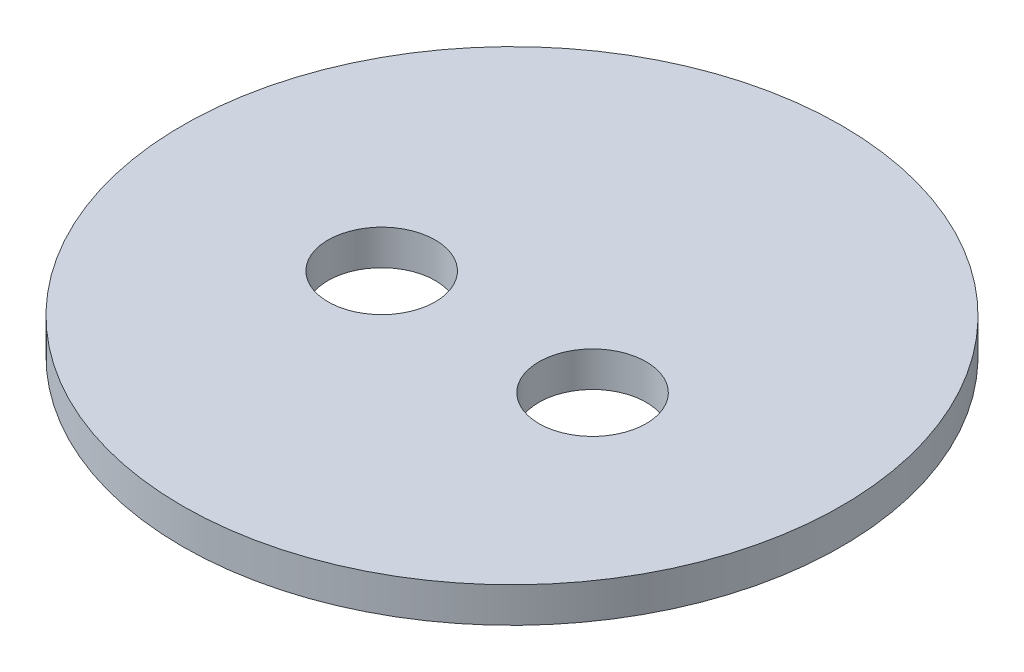
SolidWorks part; units mm, degrees
ref_plane "Front Plane" through (0, 0, 0) normal (0, 0, 1) x (1, 0, 0)
ref_plane "Top Plane" through (0, 0, 0) normal (0, 1, 0) x (1, 0, 0)
ref_plane "Right Plane" through (0, 0, 0) normal (1, 0, 0) x (0, 0, -1)
sketch "Sketch1" plane through (0, 0, 0) normal (0, 1, 0) x (1, 0, 0)
  circle A0 centre (0, 0) radius 9.375
  dimension "D1" = 18.75
extrude "Boss-Extrude1" add sketch "Sketch1" along normal blind 1
sketch "Sketch2" plane through (0, 1, 0) normal (0, 1, 0) x (1, 0, 0)
  line L0 (-10.2256, 0) -> (10.3097, 0) construction
  line L1 (0.0421, 9.2577) -> (0.0421, -9.7417) construction
  line L2 (-10.2256, -0.75) -> (10.3097, -0.75) construction
  circle A0 centre (3.0421, -0.75) radius 1.525
  circle A1 centre (-2.9579, -0.75) radius 1.525
  circle A2 centre (0, 0) radius 9.375 construction
  point P11 (0, 9.375)
  dimension "D2" = 3.05
  dimension "D1" = 0.75
  dimension "D3" = 3
extrude "Cut-Extrude1" cut sketch "Sketch2" against normal through all
